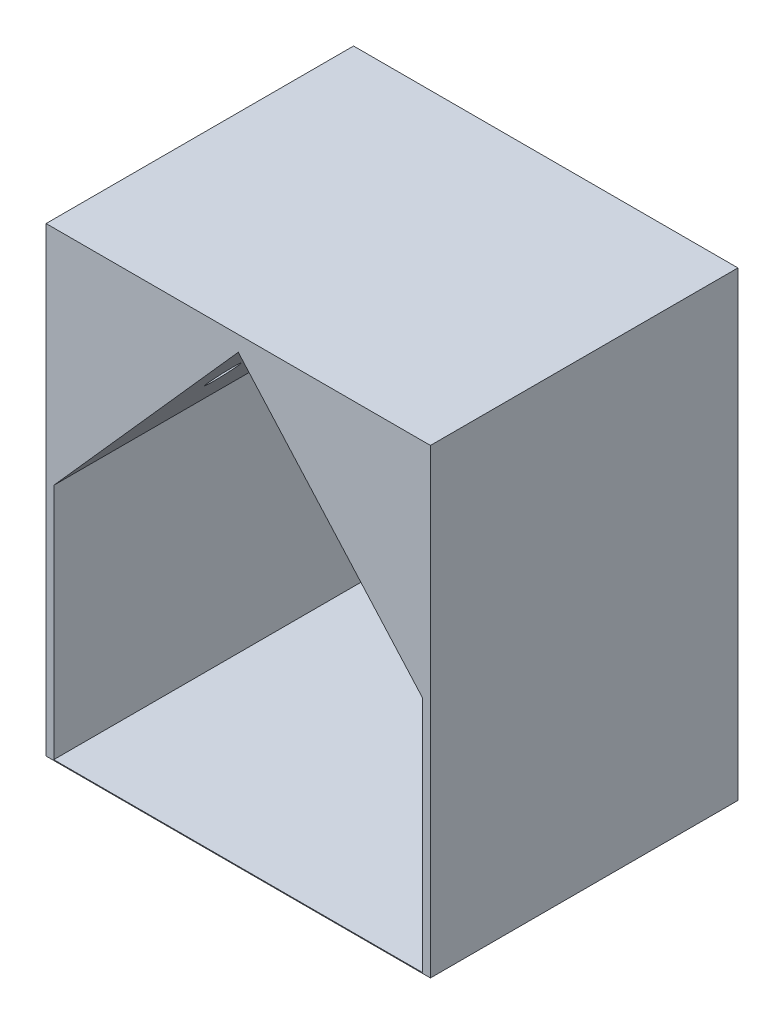
SolidWorks part; units mm, degrees
ref_plane "Front Plane" through (0, 0, 0) normal (0, 0, 1) x (1, 0, 0)
ref_plane "Top Plane" through (0, 0, 0) normal (0, 1, 0) x (1, 0, 0)
ref_plane "Right Plane" through (0, 0, 0) normal (1, 0, 0) x (0, 0, -1)
sketch "Sketch1" plane through (0, 0, 0) normal (0, 0, 1) x (1, 0, 0)
  line L0 (-1599.1508, 0) -> (1757.5573, 0) construction
  line L1 (0, 899.5223) -> (0, -922.1518) construction
  line L3 (1250, -1500) -> (-1250, -1500)
  line L4 (1250, -1500) -> (1250, 1500)
  line L5 (1250, 1500) -> (-1250, 1500)
  line L6 (-1250, -1500) -> (-1250, 1500)
  line L7 (1250, -1500) -> (-1250, 1500) construction
  line L8 (1250, 1500) -> (-1250, -1500) construction
  point P5 (0, 0)
  dimension "D1" = 2500
  dimension "D2" = 3000
extrude "Boss-Extrude1" add sketch "Sketch1" along normal blind 2000
sketch "Sketch2" plane through (0, 0, 2000) normal (0, 0, 1) x (1, 0, 0)
  line L0 (-1200, -1495) -> (-1200, 50.5007)
  line L1 (1250, 1500) -> (-1250, 1500) construction
  line L2 (-1250, -1500) -> (1250, -1500) construction
  line L4 (-1200, 50.5007) -> (0, 1400)
  line L5 (0, 1400) -> (1200, 50.5007)
  line L6 (1200, 50.5007) -> (1200, -1495)
  line L7 (0, 490.3915) -> (0, -1315.4735) construction
  line L8 (-1250, 1500) -> (-1250, -1500) construction
  line L9 (-1200, -1495) -> (1200, -1495)
  dimension "D1" = 50
  dimension "D2" = 2400
  dimension "D3" = 5
  dimension "D4" = 100
extrude "Cut-Extrude4" cut sketch "Sketch2" against normal blind 1995 and the other way through all
sketch "Sketch3" plane through (-695.2026, 618.1871, 0) normal (0.7473, -0.6645, 0) x (0.6645, 0.7473, 0)
  line L0 (143.2692, 2000) -> (143.2692, 0) construction
  line L1 (-759.6633, 2000) -> (1046.2017, 2000) construction
  line L2 (-759.6633, 0) -> (1046.2017, 0) construction
  line L3 (-759.6633, 1002.5) -> (1046.2017, 1002.5) construction
  line L4 (-759.6633, 5) -> (-759.6633, 2000) construction
  line L5 (1046.2017, 5) -> (1046.2017, 2000) construction
  line L6 (-759.6633, 1500) -> (1046.2017, 1500) construction
  line L7 (-759.6633, 502.5) -> (1046.2017, 502.5) construction
  circle A0 centre (143.2692, 1500) radius 100
  circle A1 centre (143.2692, 1000) radius 100
  circle A2 centre (143.2692, 502.5) radius 100
  dimension "D1" = 500
  dimension "D2" = 500
sketch "Sketch6" plane through (695.2026, 618.1871, 0) normal (-0.7473, -0.6645, 0) x (0.6645, -0.7473, 0)
  line L0 (-1046.2017, 1500) -> (759.6633, 1500) construction
  line L1 (759.6633, 5) -> (759.6633, 2000) construction
  line L2 (-1046.2017, 1002.5) -> (759.6633, 1002.5) construction
  line L3 (-1046.2017, 502.5) -> (759.6633, 502.5) construction
  line L4 (-143.2692, 2000) -> (-143.2692, 0) construction
  line L5 (-1046.2017, 2000) -> (759.6633, 2000) construction
  line L6 (-1046.2017, 0) -> (759.6633, 0) construction
  circle A0 centre (-143.2692, 1500) radius 100
  circle A1 centre (-143.2692, 1002.5) radius 100
  circle A2 centre (-143.2692, 502.5) radius 100
extrude "Cut-Extrude5" cut sketch "Sketch6" against normal blind 20
extrude "Cut-Extrude6" cut sketch "Sketch3" against normal blind 20
